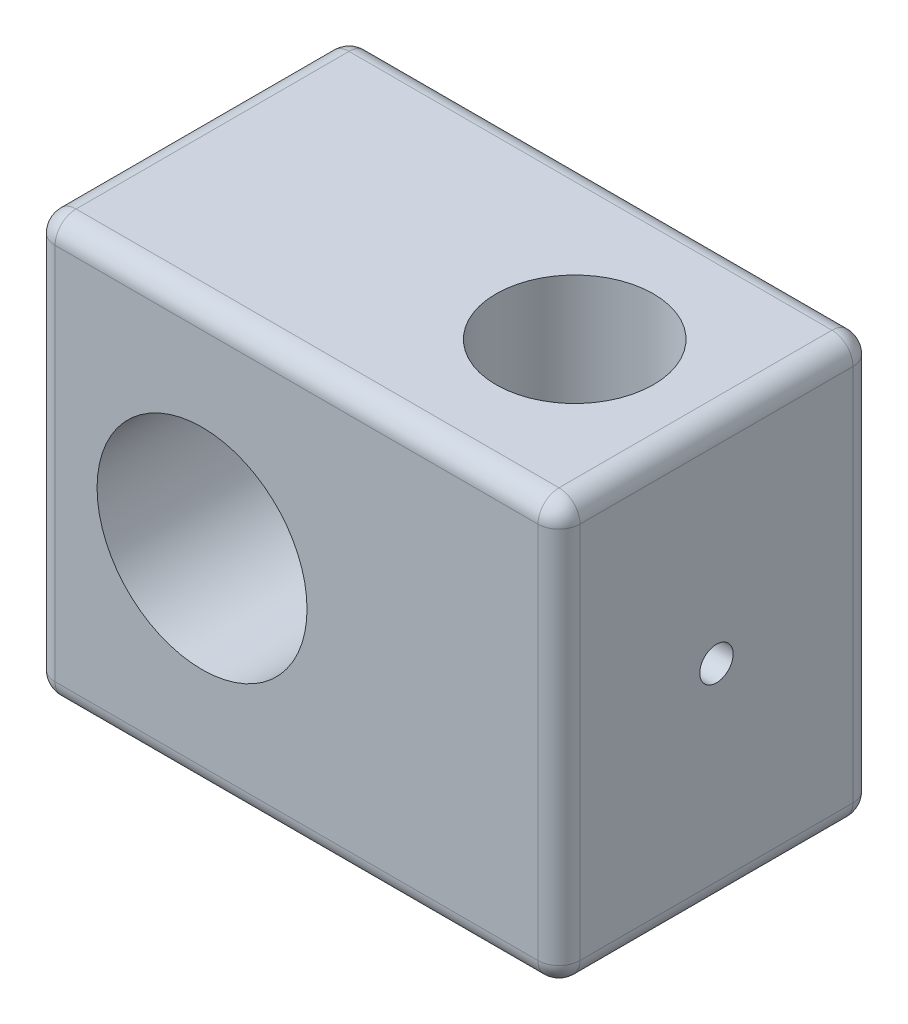
SolidWorks part; units mm, degrees
ref_plane "Front Plane" through (0, 0, 0) normal (0, 0, 1) x (1, 0, 0)
ref_plane "Top Plane" through (0, 0, 0) normal (0, 1, 0) x (1, 0, 0)
ref_plane "Right Plane" through (0, 0, 0) normal (1, 0, 0) x (0, 0, -1)
sketch "Croquis1" plane through (0, 0, 0) normal (0, 1, 0) x (1, 0, 0)
  line L1 (-31.75, 19.05) -> (31.75, 19.05)
  line L2 (-31.75, 19.05) -> (-31.75, -19.05)
  line L3 (-31.75, -19.05) -> (31.75, -19.05)
  line L4 (31.75, 19.05) -> (31.75, -19.05)
  line L5 (-31.75, 19.05) -> (31.75, -19.05) construction
  line L6 (-31.75, -19.05) -> (31.75, 19.05) construction
  point P0 (0, 0)
  dimension "D1" = 38.1
  dimension "D2" = 63.5
extrude "Saliente-Extruir1" add sketch "Croquis1" along normal blind 50.8
sketch "Croquis2" plane through (0, 0, 19.05) normal (0, 0, 1) x (1, 0, 0)
  line L0 (-31.75, 25.4) -> (31.75, 25.4) construction
  line L1 (-31.75, 50.8) -> (-31.75, 0) construction
  line L2 (31.75, 50.8) -> (31.75, 0) construction
  line L3 (0, 50.8) -> (0, 0) construction
  line L4 (-31.75, 50.8) -> (31.75, 50.8) construction
  circle A0 centre (-11.43, 25.4) radius 12.7
  point P13 (-24.13, 25.4)
  dimension "D1" = 25.4
  dimension "D2" = 7.62
extrude "Cortar-Extruir1" cut sketch "Croquis2" against normal blind 63.5
sketch "Croquis3" plane through (0, 50.8, 0) normal (0, 1, 0) x (1, 0, 0)
  line L0 (-31.75, 0) -> (31.75, 0) construction
  line L1 (-31.75, 19.05) -> (-31.75, -19.05) construction
  line L2 (31.75, -19.05) -> (31.75, 19.05) construction
  circle A0 centre (14.605, 0) radius 9.525
  point P8 (24.13, 0)
  dimension "D1" = 7.62
  dimension "D2" = 19.05
extrude "Cortar-Extruir2" cut sketch "Croquis3" against normal blind 63.5
fillet "Redondeo1" radius 2.54 12 edges at (-31.75, 25.4, -19.05) (-31.75, 25.4, 19.05) (0, 0, 19.05) (0, 0, -19.05) (-31.75, 0, 0) (-31.75, 50.8, 0) (0, 50.8, -19.05) (0, 50.8, 19.05) (31.75, 25.4, -19.05) (31.75, 25.4, 19.05) (31.75, 0, 0) (31.75, 50.8, 0)
hole_wizard "Taladro roscado #10-322" positions "Croquis5" profile "Croquis4" tap size "#10-32" standard "Ansi Inch"
sketch "Croquis5" plane through (31.75, 0, 0) normal (1, 0, 0) x (0, 0, -1)
  line L0 (0, 48.26) -> (0, 2.54) construction
  line L1 (16.51, 48.26) -> (-16.51, 48.26) construction
  line L2 (-16.51, 2.54) -> (16.51, 2.54) construction
  line L3 (-16.51, 25.4) -> (16.51, 25.4) construction
  line L4 (-16.51, 48.26) -> (-16.51, 2.54) construction
  line L5 (16.51, 2.54) -> (16.51, 48.26) construction
  point P0 (0, 25.4)
sketch "Croquis4" plane through (31.75, 25.4, 0) normal (0, 1, 0) x (0, 0, -1)
  line L0 (0, 0) -> (0, 14.8277)
  line L1 (0, 14.8277) -> (2.0193, 13.6144)
  line L2 (2.0193, 13.6144) -> (2.0193, 0)
  line L5 (2.0193, 0) -> (0, 0)
  line L10 (0, 14.8277) -> (-2.0193, 13.6144) construction
  line L11 (0, -6.35) -> (0, 107.95) construction
  dimension "Diámetro de perforador para roscar" = 4.0386
  dimension "Profundidad de perforador para roscar" = 13.6144
  dimension "Ángulo de perforador" = 118
cosmetic thread "Rosca de taladro1" parameters "D1"=7.7816, "D2"=4.826
hole_wizard "Taladro roscado #10-321" positions "Croquis7" profile "Croquis6" tap size "#10-32" standard "Ansi Inch"
sketch "Croquis7" plane through (-31.75, 0, 0) normal (-1, 0, 0) x (0, 0, 1)
  line L0 (0, 0) -> (0, 48.26) construction
  line L1 (16.51, 48.26) -> (-16.51, 48.26) construction
  line L2 (-16.51, 25.4) -> (16.51, 25.4) construction
  line L3 (-16.51, 48.26) -> (-16.51, 2.54) construction
  line L4 (16.51, 2.54) -> (16.51, 48.26) construction
  point P0 (0, 25.4)
sketch "Croquis6" plane through (-31.75, 25.4, 0) normal (0, 1, 0) x (0, 0, 1)
  line L0 (0, 0) -> (0, 14.8277)
  line L1 (0, 14.8277) -> (2.0193, 13.6144)
  line L2 (2.0193, 13.6144) -> (2.0193, 0)
  line L5 (2.0193, 0) -> (0, 0)
  line L10 (0, 14.8277) -> (-2.0193, 13.6144) construction
  line L11 (0, -6.35) -> (0, 107.95) construction
  dimension "Diámetro de perforador para roscar" = 4.0386
  dimension "Profundidad de perforador para roscar" = 13.6144
  dimension "Ángulo de perforador" = 118
cosmetic thread "Rosca de taladro2" parameters "D1"=7.7004, "D2"=4.826
sketch "Croquis8" plane through (0, 50.8, 0) normal (0, 1, 0) x (1, 0, 0)
  line L0 (-11.43, -33.1621) -> (-11.43, 42.6082) construction
  line L2 (1.27, -19.05) -> (1.27, 19.05) construction
  line L12 (-24.13, 19.05) -> (-24.13, 2.0193) construction
  point P16 (14.605, 0)
  dimension "D1" = 26.035
